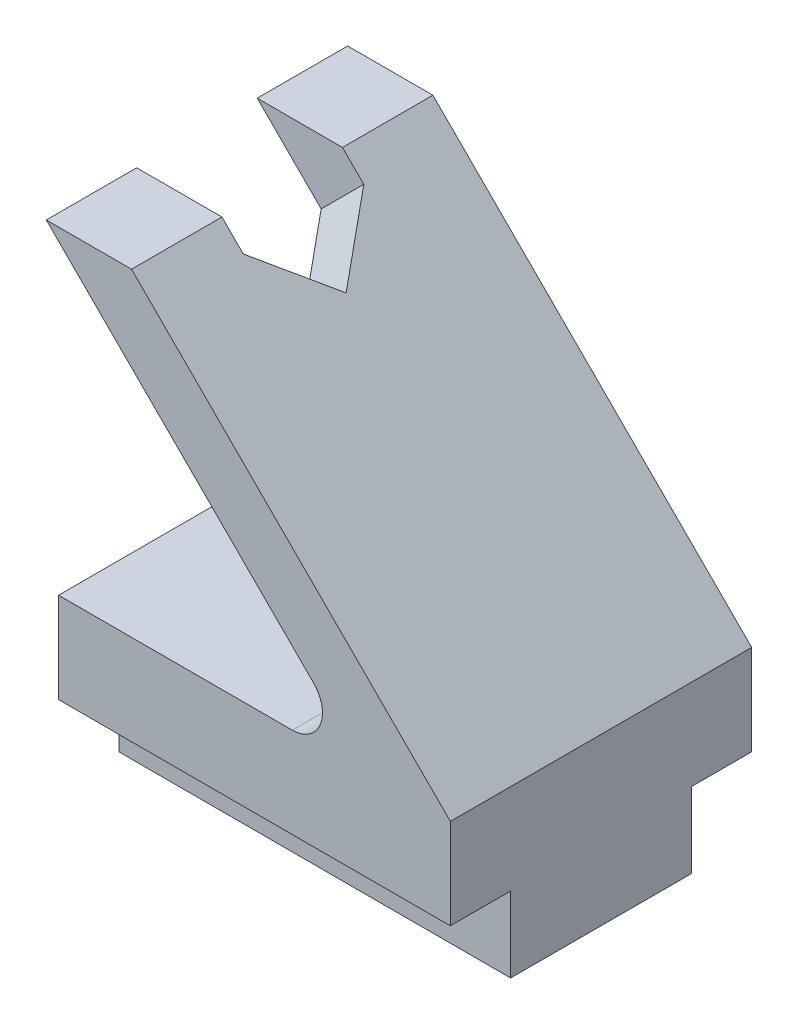
SolidWorks part; units mm, degrees
ref_plane "前基準面" through (0, 0, 0) normal (0, 0, 1) x (1, 0, 0)
ref_plane "上基準面" through (0, 0, 0) normal (0, 1, 0) x (1, 0, 0)
ref_plane "右基準面" through (0, 0, 0) normal (1, 0, 0) x (0, 0, -1)
sketch "草圖2" plane through (0, 0, 0) normal (0, 0, 1) x (1, 0, 0)
  line L0 (0, 0) -> (52, 0)
  line L1 (52, 0) -> (52, 22)
  line L4 (52, 22) -> (9.6835, 64.3165)
  line L5 (9.6835, 64.3165) -> (-1.6302, 64.3165)
  line L6 (-1.6302, 64.3165) -> (33.8579, 28.8284)
  line L7 (0, 0) -> (0, 22)
  line L8 (0, 22) -> (31.0294, 22)
  arc A0 (33.8579, 28.8284) -> (31.0294, 22) centre (31.0294, 26) cw
  dimension "D1" = 4
  dimension "D3" = 22
  dimension "D2" = 135
  dimension "D4" = 22
  dimension "D5" = 8
  dimension "D6" = 59.8446
  dimension "D7" = 52
extrude "填料-伸長1" add sketch "草圖2" against normal blind 40
sketch "草圖4" plane through (0, 0, 0) normal (0, 0, 1) x (1, 0, 0)
  line L0 (0, 0) -> (52, 0)
  line L1 (0, 0) -> (0, 10)
  line L3 (0, 10) -> (52, 10)
  line L4 (0, 22) -> (0, 0) construction
  line L6 (52, 0) -> (52, 22) construction
  line L7 (52, 10) -> (52, 0)
  dimension "D1" = 10
extrude "除料-伸長1" cut sketch "草圖4" against normal blind 8
sketch "草圖7" plane through (0, 0, -40) normal (0, 0, -1) x (-1, 0, 0)
  line L0 (-52, 0) -> (-52, 10)
  line L1 (-52, 0) -> (-52, 22) construction
  line L2 (-52, 10) -> (0, 10)
  line L3 (0, 10) -> (0, 0)
  line L4 (0, 0) -> (-52, 0)
  dimension "D1" = 10
extrude "除料-伸長2" cut sketch "草圖7" against normal blind 8
sketch "草圖8" plane through (0, 0, 0) normal (0, 1, 0) x (1, 0, 0)
  line L0 (-1.6302, 0) -> (-1.6302, 12.2763)
  line L1 (-1.6302, 40) -> (-1.6302, 0) construction
  line L2 (-1.6302, 12.2763) -> (9.6835, 12.2763)
  line L3 (9.6835, 40) -> (9.6835, 0) construction
  line L4 (9.6835, 12.2763) -> (21.2451, 12.2763)
  line L5 (21.2451, 12.2763) -> (29.2451, 20.2763)
  line L6 (29.2451, 20.2763) -> (21.2451, 28.2763)
  line L7 (21.2451, 28.2763) -> (9.6835, 28.2763)
  line L8 (9.6835, 28.2763) -> (-1.6302, 28.2763)
  line L9 (-1.6302, 28.2763) -> (-1.6302, 12.2763)
  line L10 (-1.6302, 28.2763) -> (-1.6302, 12.2763)
  dimension "D1" = 11.5616
  dimension "D2" = 11.5616
  dimension "D3" = 11.3137
  dimension "D4" = 11.3137
  dimension "D5" = 16
  dimension "D6" = 11.3137
sketch "草圖9" plane through (37, 37, 0) normal (0.7071, 0.7071, 0) x (0, 0, -1)
  line L0 (12, 46.6314) -> (12, 34.6314)
  line L1 (40, 46.6314) -> (0, 46.6314) construction
  line L2 (12, 34.6314) -> (20, 26.6314)
  line L3 (20, 26.6314) -> (28, 34.6314)
  line L4 (28, 34.6314) -> (28, 46.6314)
  line L5 (20, -36.7696) -> (20, 51.5717) construction
  line L6 (32, -36.7696) -> (8, -36.7696) construction
  dimension "D1" = 20
  dimension "D2" = 16
extrude "除料-伸長3" cut sketch "草圖9" along normal through all and the other way through all
